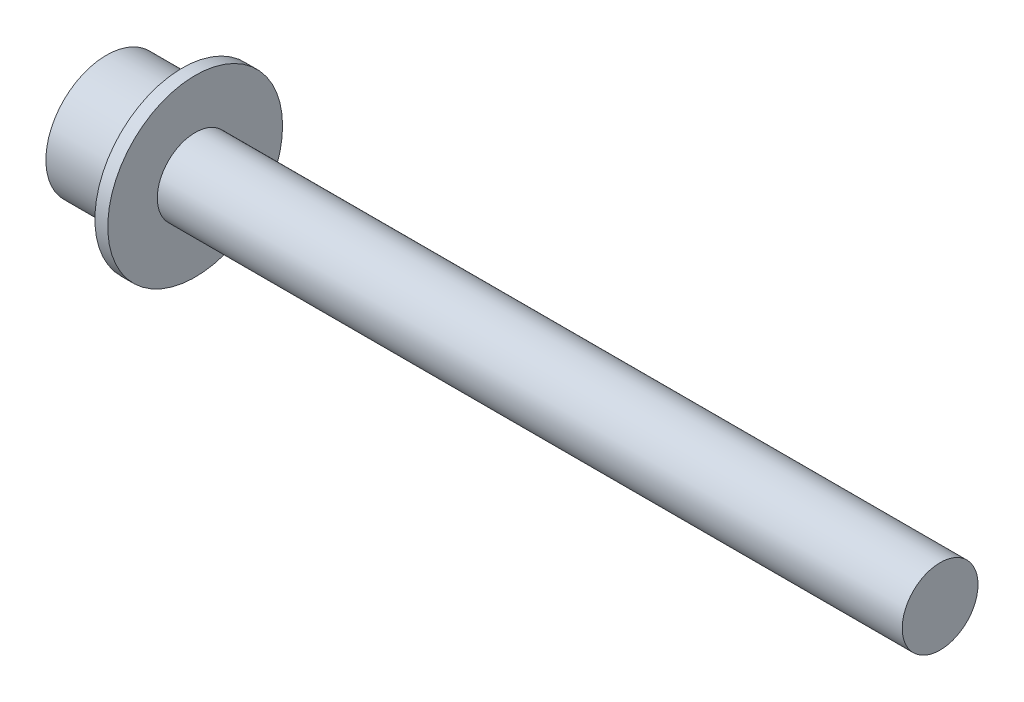
SolidWorks part; units mm, degrees
ref_plane "Front Plane" through (0, 0, 0) normal (0, 0, 1) x (1, 0, 0)
ref_plane "Top Plane" through (0, 0, 0) normal (0, 1, 0) x (1, 0, 0)
ref_plane "Right Plane" through (0, 0, 0) normal (1, 0, 0) x (0, 0, -1)
other "Configuration Table"
sketch "Sketch1" plane through (0, 0, 0) normal (1, 0, 0) x (0, 0, -1)
  circle A0 centre (0, 0) radius 2.4
  dimension "D1" = 4.8
extrude "Boss-Extrude1" add sketch "Sketch1" along normal blind 3
sketch "Sketch2" plane through (3, 0, 0) normal (1, 0, 0) x (0, 0, -1)
  circle A0 centre (0, 0) radius 1.5
  dimension "D1" = 3
extrude "Boss-Extrude2" add sketch "Sketch2" along normal blind 30
sketch "Sketch3" plane through (3, 0, 0) normal (1, 0, 0) x (0, 0, -1)
  circle A0 centre (0, 0) radius 3.46
  dimension "D1" = 6.92
extrude "Boss-Extrude3" add sketch "Sketch3" along normal blind 0.51
